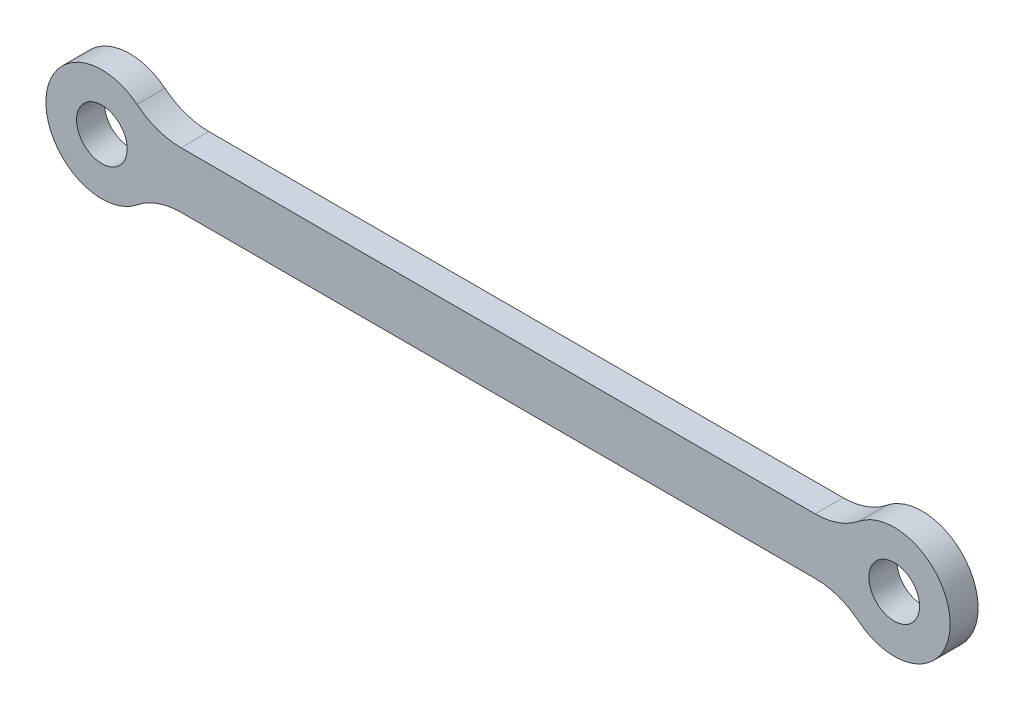
SolidWorks part; units mm, degrees
ref_plane "Front Plane" through (0, 0, 0) normal (0, 0, 1) x (1, 0, 0)
ref_plane "Top Plane" through (0, 0, 0) normal (0, 1, 0) x (1, 0, 0)
ref_plane "Right Plane" through (0, 0, 0) normal (1, 0, 0) x (0, 0, -1)
sketch "Sketch1" plane through (0, 0, 0) normal (0, 0, 1) x (1, 0, 0)
  line L0 (-26.2008, 0) -> (165.4129, 0) construction
  line L1 (14.3684, 5.08) -> (129.5649, 5.08)
  line L2 (14.3684, -5.08) -> (129.5649, -5.08)
  circle A0 centre (0, 0) radius 4.6037
  arc A1 (6.386, 7.9022) -> (6.386, -7.9022) centre (0, 0) ccw
  circle A2 centre (143.9333, 0) radius 4.6037
  arc A3 (137.5474, -7.9022) -> (137.5474, 7.9022) centre (143.9333, 0) ccw
  arc A4 (137.5474, 7.9022) -> (129.5649, 5.08) centre (129.5649, 17.78) cw
  arc A5 (129.5649, -5.08) -> (137.5474, -7.9022) centre (129.5649, -17.78) cw
  arc A6 (14.3684, -5.08) -> (6.386, -7.9022) centre (14.3684, -17.78) ccw
  arc A7 (14.3684, 5.08) -> (6.386, 7.9022) centre (14.3684, 17.78) cw
  point P14 (135.1345, 5.08)
  point P17 (135.1345, -5.08)
  point P20 (8.7988, -5.08)
  point P23 (8.7988, 5.08)
  dimension "D1" = 9.2075
  dimension "D2" = 20.32
  dimension "D3" = 20.32
  dimension ".3625" = 9.2075
  dimension "D7" = 12.7
  dimension "D5" = 143.9333
  dimension "D6" = 5.08
extrude "Boss-Extrude1" add sketch "Sketch1" along normal blind 5.08
